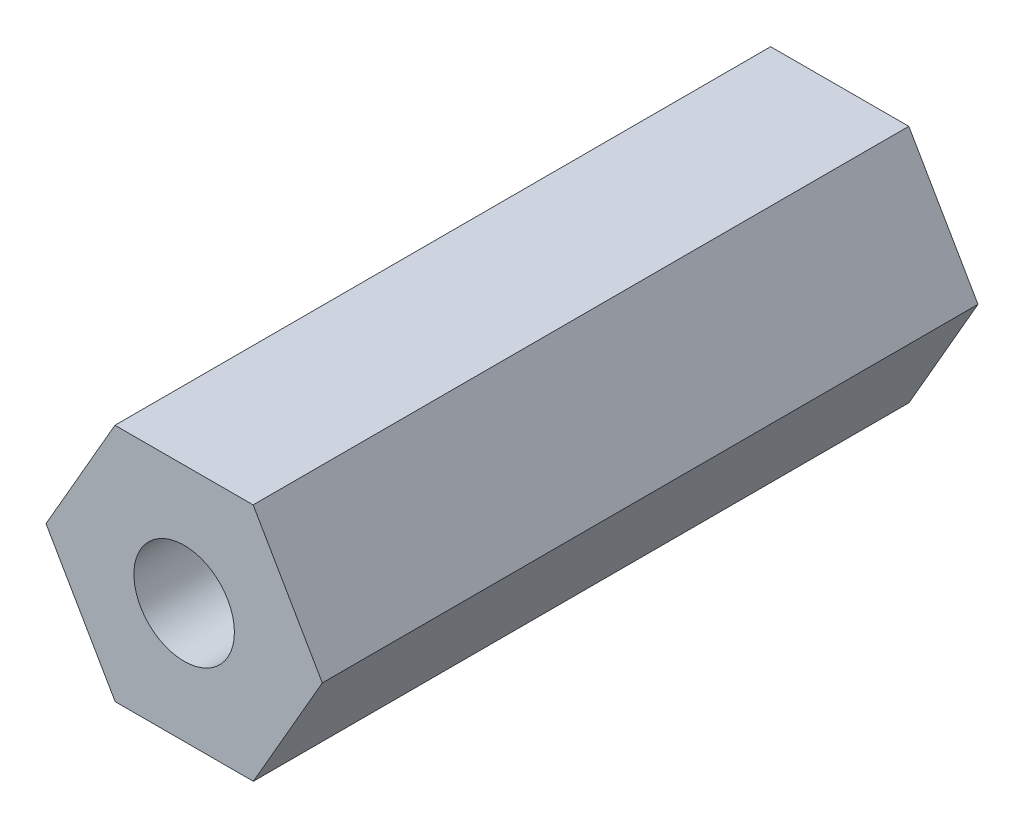
SolidWorks part; units mm, degrees
ref_plane "Front Plane" through (0, 0, 0) normal (0, 0, 1) x (1, 0, 0)
ref_plane "Top Plane" through (0, 0, 0) normal (0, 1, 0) x (1, 0, 0)
ref_plane "Right Plane" through (0, 0, 0) normal (1, 0, 0) x (0, 0, -1)
sketch "Sketch1" plane through (0, 0, 0) normal (0, 0, 1) x (1, 0, 0)
  line L1 (3.672, -6.0066) -> (7.3323, 0.3467)
  line L2 (7.3323, 0.3467) -> (3.6604, 6.6934)
  line L3 (3.6604, 6.6934) -> (-3.672, 6.6866)
  line L4 (-3.672, 6.6866) -> (-7.3323, 0.3333)
  line L5 (-7.3323, 0.3333) -> (-3.6604, -6.0134)
  line L6 (-3.6604, -6.0134) -> (3.672, -6.0066)
  circle A0 centre (0, 0.34) radius 6.35 construction
  circle A1 centre (0, 0.34) radius 2.667
  dimension "D1" = 12.7
extrude "Boss-Extrude1" add sketch "Sketch1" along normal blind 34.798
